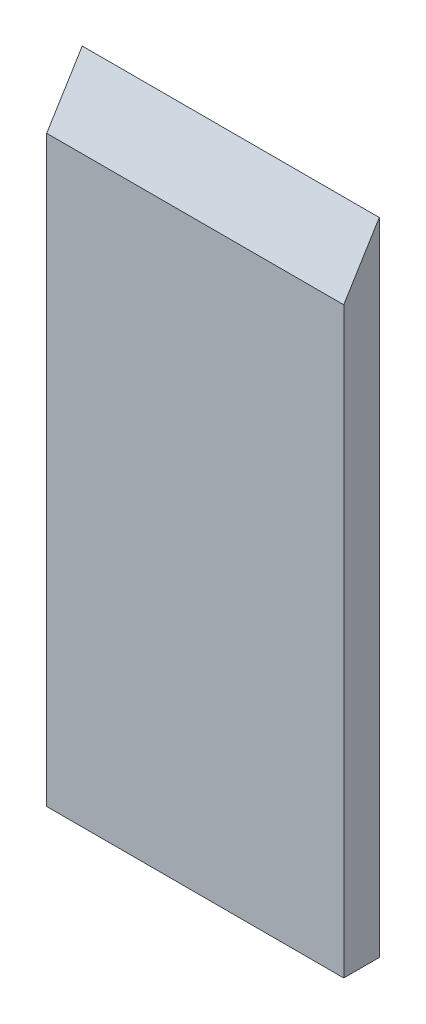
SolidWorks part; units mm, degrees
ref_plane "Alzado" through (0, 0, 0) normal (0, 0, 1) x (1, 0, 0)
ref_plane "Planta" through (0, 0, 0) normal (0, 1, 0) x (1, 0, 0)
ref_plane "Vista lateral" through (0, 0, 0) normal (1, 0, 0) x (0, 0, -1)
sketch "Croquis1" plane through (0, 0, 0) normal (0, 1, 0) x (1, 0, 0)
  line L1 (-169.4219, 44.6777) -> (190.0781, 44.6777)
  line L2 (-169.4219, 44.6777) -> (-169.4219, 1.6777)
  line L3 (-169.4219, 1.6777) -> (190.0781, 1.6777)
  line L4 (190.0781, 44.6777) -> (190.0781, 1.6777)
  dimension "D1" = 359.5
  dimension "D2" = 43
extrude "Saliente-Extruir1" add sketch "Croquis1" along normal blind 775.633
sketch "Croquis5" plane through (190.0781, 0, 0) normal (1, 0, 0) x (0, 0, -1)
  line L0 (44.6777, 775.633) -> (1.6777, 705.6376)
  line L1 (1.6777, 775.633) -> (1.6777, 0) construction
  line L2 (1.6777, 705.6376) -> (1.6777, 775.633)
  line L3 (1.6777, 775.633) -> (44.6777, 775.633)
  line L4 (44.6777, 775.633) -> (44.6777, 0) construction
  dimension "D1" = 31.563
extrude "Cortar-Extruir1" cut sketch "Croquis5" against normal blind 360
